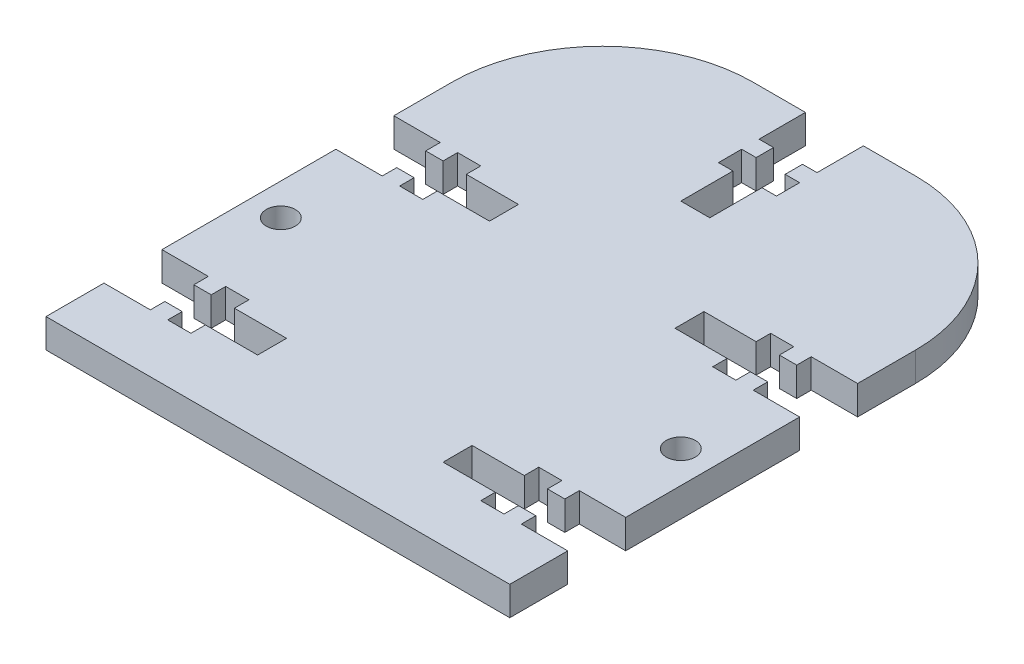
SolidWorks part; units mm, degrees
material "Acrylic (Medium-high impact)"
ref_plane "Front Plane" through (0, 0, 0) normal (0, 0, 1) x (1, 0, 0)
ref_plane "Top Plane" through (0, 0, 0) normal (0, 1, 0) x (1, 0, 0)
ref_plane "Right Plane" through (0, 0, 0) normal (1, 0, 0) x (0, 0, -1)
sketch "Sketch1" plane through (0, 0, 0) normal (0, 1, 0) x (1, 0, 0)
  line L1 (-25.4, 30.48) -> (25.4, 30.48)
  line L2 (-25.4, 30.48) -> (-25.4, -30.48)
  line L3 (-25.4, -30.48) -> (25.4, -30.48)
  line L4 (25.4, 30.48) -> (25.4, -30.48)
  line L5 (-25.4, 30.48) -> (25.4, -30.48) construction
  line L6 (-25.4, -30.48) -> (25.4, 30.48) construction
  point P0 (0, 0)
  dimension "D1" = 50.8
  dimension "D2" = 60.96
extrude "Boss-Extrude2" add sketch "Sketch1" along normal blind 3.175
sketch "Sketch5" plane through (0, 3.175, 0) normal (0, 1, 0) x (1, 0, 0)
  line L0 (-20.32, 6.0325) -> (-18.415, 6.0325)
  line L1 (-25.4, 30.48) -> (-25.4, 7.62) construction
  line L2 (-20.32, 2.8575) -> (-18.415, 2.8575)
  line L3 (-18.415, 2.8575) -> (-18.415, 1.27)
  line L4 (-18.415, 1.27) -> (-15.875, 1.27)
  line L5 (-15.875, 1.27) -> (-15.875, 2.8575)
  line L6 (-15.875, 2.8575) -> (-10.16, 2.8575)
  line L7 (-10.16, 2.8575) -> (-10.16, 6.0325)
  line L8 (-10.16, 6.0325) -> (-15.875, 6.0325)
  line L9 (-15.875, 6.0325) -> (-15.875, 7.62)
  line L10 (-15.875, 7.62) -> (-18.415, 7.62)
  line L11 (-18.415, 7.62) -> (-18.415, 6.0325)
  line L12 (-25.4, 7.62) -> (-20.32, 7.62)
  line L13 (-25.4, 7.62) -> (-25.4, 1.27)
  line L14 (-20.32, 7.62) -> (-20.32, 6.0325)
  line L15 (-25.4, 1.27) -> (-20.32, 1.27)
  line L16 (-20.32, 1.27) -> (-20.32, 2.8575)
  line L17 (-25.4, 30.48) -> (-25.4, -30.48) construction
  point P27 (-17.145, 7.62)
  dimension "D1" = 3.175
  dimension "D2" = 6.35
  dimension "D3" = 2.54
  dimension "D4" = 5.08
  dimension "D5" = 10.16
  dimension "D6" = 22.86
  dimension "D7" = 6.35
  dimension "D8" = 3.175
extrude "Cut-Extrude3" cut sketch "Sketch5" against normal through all
pattern_linear "LPattern3" count 2 spacing 25.4 along (0, 0, 1) of "Cut-Extrude3"
sketch "Sketch6" plane through (0, 3.175, 0) normal (0, 1, 0) x (1, 0, 0)
  line L0 (-20.32, 1.27) -> (-23.495, 1.27) construction
  line L1 (-25.4, 1.27) -> (-20.32, 1.27) construction
  line L2 (-21.9075, 1.27) -> (-21.9075, -17.78) construction
  line L3 (-20.32, -17.78) -> (-25.4, -17.78) construction
  circle A0 centre (-21.9075, -8.255) radius 1.5875
  point P11 (0, 0)
  dimension "D2" = 3.175
  dimension "D1" = 3.175
extrude "Cut-Extrude4" cut sketch "Sketch6" against normal through all
mirror "Mirror4" about plane through (0, 0, 0) normal (1, 0, 0) of "LPattern3", "Cut-Extrude4", "Cut-Extrude3"
sketch "Sketch7" plane through (0, 3.175, 0) normal (0, 1, 0) x (1, 0, 0)
  line L0 (-3.175, 30.48) -> (-3.175, 25.4)
  line L1 (25.4, 30.48) -> (-25.4, 30.48) construction
  line L2 (-3.175, 25.4) -> (-1.5875, 25.4)
  line L3 (-1.5875, 25.4) -> (-1.5875, 23.495)
  line L4 (-1.5875, 23.495) -> (-3.175, 23.495)
  line L5 (-3.175, 23.495) -> (-3.175, 20.955)
  line L6 (-3.175, 20.955) -> (-1.5875, 20.955)
  line L7 (-1.5875, 20.955) -> (-1.5875, 15.24)
  line L8 (-1.5875, 15.24) -> (1.5875, 15.24)
  line L9 (1.5875, 15.24) -> (1.5875, 20.955)
  line L10 (1.5875, 20.955) -> (3.175, 20.955)
  line L11 (3.175, 20.955) -> (3.175, 23.495)
  line L12 (3.175, 23.495) -> (1.5875, 23.495)
  line L13 (1.5875, 23.495) -> (1.5875, 25.4)
  line L14 (1.5875, 25.4) -> (3.175, 25.4)
  line L15 (3.175, 25.4) -> (3.175, 30.48)
  line L16 (3.175, 30.48) -> (-3.175, 30.48)
  line L17 (-25.4, 30.48) -> (0, 30.48) construction
  line L18 (3.175, 25.4) -> (3.175, 22.225) construction
  point P16 (-1.5875, 10.6253)
  point P22 (3.175, 10.2559)
  point P23 (0, 0)
  dimension "D1" = 6.35
  dimension "D2" = 25.4
  dimension "D3" = 3.175
  dimension "D4" = 3.175
  dimension "D5" = 6.35
  dimension "D6" = 5.08
  dimension "D7" = 10.16
  dimension "D8" = 3.175
  dimension "D9" = 2.54
extrude "Cut-Extrude5" cut sketch "Sketch7" against normal through all
sketch "Sketch10" plane through (0, 3.175, 0) normal (0, 1, 0) x (1, 0, 0)
  line L0 (-25.4, 13.97) -> (-25.4, 30.48)
  line L1 (-25.4, 30.48) -> (-8.89, 30.48)
  line L2 (-3.175, 30.48) -> (-25.4, 30.48) construction
  line L3 (25.4, 13.97) -> (25.4, 30.48)
  line L4 (25.4, 30.48) -> (8.89, 30.48)
  line L5 (25.4, 30.48) -> (3.175, 30.48) construction
  line L6 (-25.4, 30.48) -> (-25.4, 7.62) construction
  arc A0 (-25.4, 13.97) -> (-8.89, 30.48) centre (-8.89, 13.97) cw
  arc A1 (25.4, 13.97) -> (8.89, 30.48) centre (8.89, 13.97) ccw
  point P7 (-25.4, 7.62)
  point P17 (9.5803, 28.575)
  point P18 (0, 0)
  point P19 (0, 0)
  point P20 (-25.4, 12.6155)
  point P23 (0, 0)
  dimension "D1" = 16.51
  dimension "D2" = 16.51
  dimension "D3" = 16.51
  dimension "D4" = 16.51
extrude "Cut-Extrude6" cut sketch "Sketch10" against normal through all
